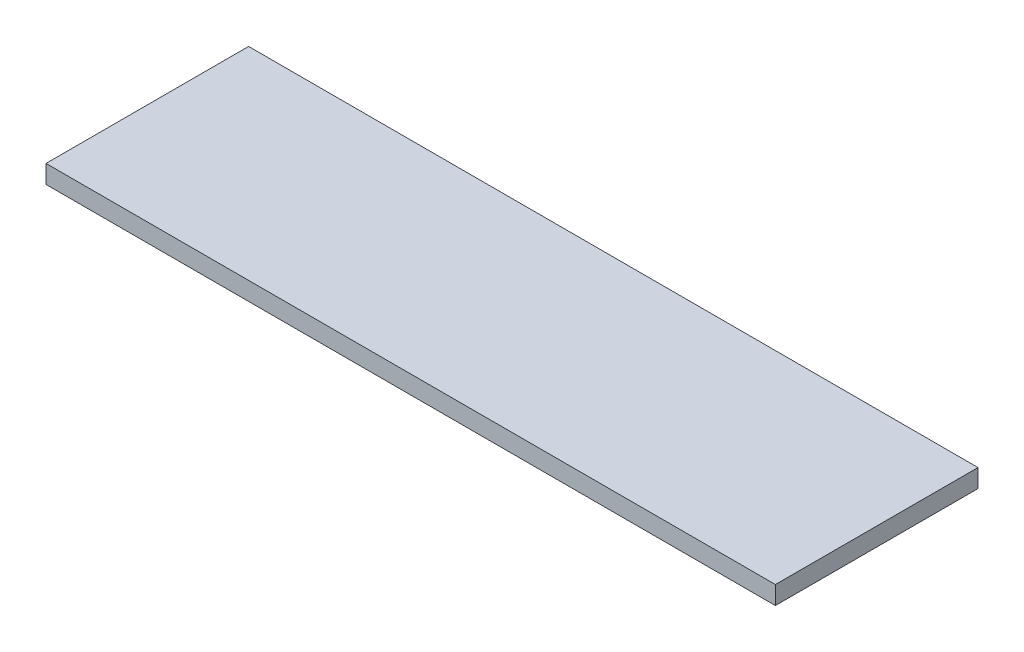
SolidWorks part; units mm, degrees
ref_plane "Front Plane" through (0, 0, 0) normal (0, 0, 1) x (1, 0, 0)
ref_plane "Top Plane" through (0, 0, 0) normal (0, 1, 0) x (1, 0, 0)
ref_plane "Right Plane" through (0, 0, 0) normal (1, 0, 0) x (0, 0, -1)
sketch "Sketch1" plane through (0, 0, 0) normal (0, 1, 0) x (1, 0, 0)
  line L1 (-360, 100) -> (360, 100)
  line L2 (-360, 100) -> (-360, -100)
  line L3 (-360, -100) -> (360, -100)
  line L4 (360, 100) -> (360, -100)
  line L5 (-360, 100) -> (360, -100) construction
  line L6 (-360, -100) -> (360, 100) construction
  point P0 (0, 0)
  dimension "D1" = 720
  dimension "D2" = 200
extrude "Boss-Extrude1" add sketch "Sketch1" along normal blind 18
